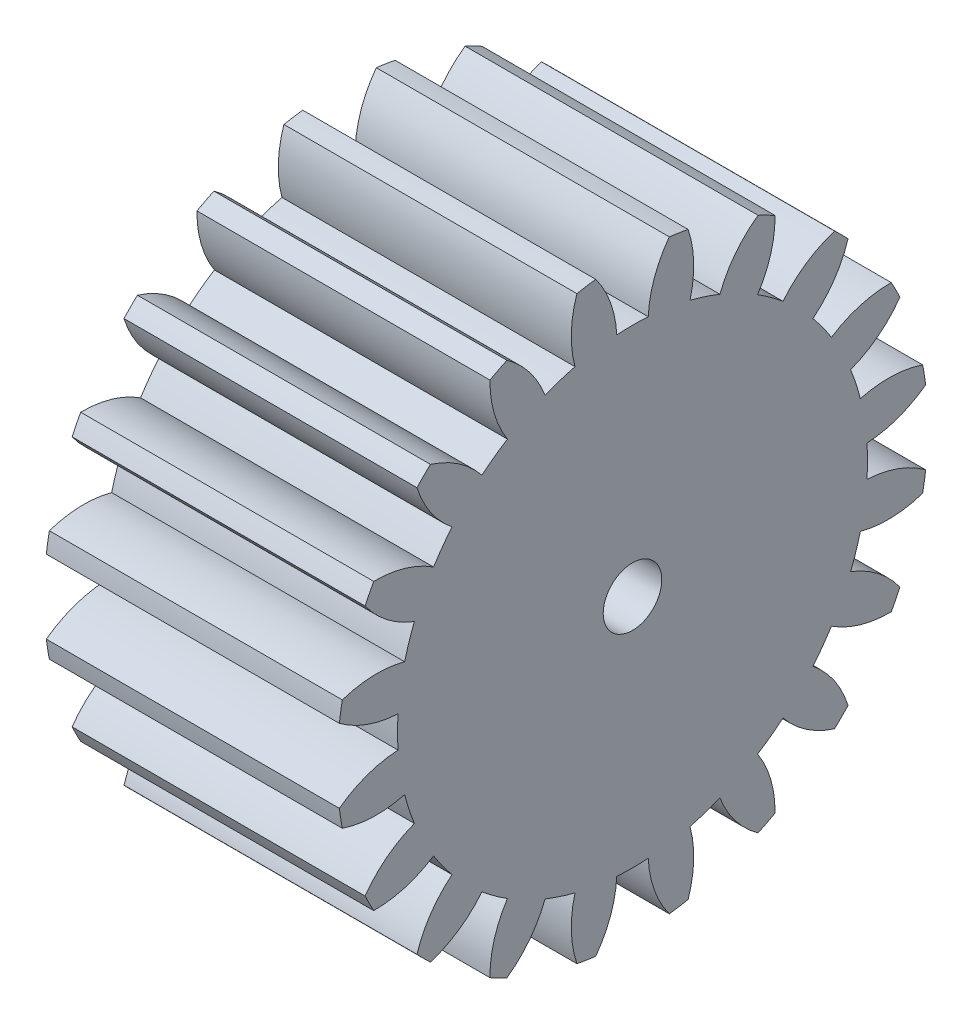
SolidWorks part; units mm, degrees
ref_plane "Plane1" through (0, 0, 0) normal (0, 0, 1) x (1, 0, 0)
ref_plane "Plane2" through (0, 0, 0) normal (0, 1, 0) x (1, 0, 0)
ref_plane "Plane3" through (0, 0, 0) normal (1, 0, 0) x (0, 0, -1)
sketch "HoldingSke" plane through (0, 0, 0) normal (0, 1, 0) x (1, 0, 0)
  line L0 (0, 0) -> (0.6834, -0.2487)
  line L1 (-15, 0) -> (100, 0) construction
  line L2 (0, 0) -> (-2.1039, 2.3779)
  line L3 (0, 0) -> (-11.863, 4.5341)
  line L4 (0, 0) -> (8.1152, 2.9537)
  line L5 (0, 0) -> (-46.8476, -17.4728)
  line L6 (0, 0) -> (-12.4344, -8.3896)
  line L7 (-2.1039, 2.3779) -> (8.6586, 51.2059)
  line L8 (-76.2, 54.61) -> (-75.7, 54.61)
  line L9 (-67.7845, 28.3722) -> (-49.3413, 33.142)
  line L10 (-76.2, 71.12) -> (104.1128, 71.12)
  line L11 (0, 0) -> (-15, 0)
  line L12 (-76.2, 101.6) -> (-76.151, 101.6)
  line L13 (24.9733, 27.94) -> (52.9518, 28.4284)
  line L14 (24.9733, 27.94) -> (24.9743, 27.94)
  line L15 (24.9733, 27.94) -> (100.4006, 29.5858)
  line L16 (-63.627, -1.375) -> (-12.827, -1.375)
  circle A0 centre (0, 0) radius 1.5
  circle A1 centre (0, 0) radius 12.0303
  circle A2 centre (0, 0) radius 37.5
  circle A3 centre (0, 0) radius 1.5
  dimension "MHD" = 24.0605
  dimension "Hub_dia" = 75
  dimension "Bore" = 3
  dimension "MBD" = 3
  dimension "Num_teeth" = 20
  dimension "Pitch" = 0.7273
  dimension "Overall_len" = 50
  dimension "Show_teeth" = 20
  dimension "Thickness" = 15
  dimension "OAL" = 50.0001
  dimension "T_dim" = 0.5
  dimension "Ap" = 14.5
  dimension "H" = 19.05
  dimension "Pitch_radius" = 180.3128
  dimension "Width" = 15
  dimension "Backlash" = 0.049
  dimension "Addendum_fac" = 1
  dimension "Dedendum_fac" = 1.25
  dimension "Clearance_fac" = 0.25
  dimension "Dedendum_add" = 0.001
  dimension "Module" = 1.375
sketch "BasProSke" plane through (0, 0, 0) normal (0, 1, 0) x (1, 0, 0)
  line L0 (-10, 0) -> (60, 0) construction
  line L1 (0, 0) -> (0, 15.125)
  line L2 (0, 0) -> (15, 0)
  line L3 (15, 0) -> (15, 15.125)
  line L4 (15, 15.125) -> (0, 15.125)
  dimension "Thickness" = 15
  dimension "Diameter" = 30.25
revolve "Base-Revolve" add sketch "BasProSke" angle 360 about L0
sketch "TooCutSke" plane through (0, 0, 0) normal (1, 0, 0) x (0, 0, -1)
  line L1 (0, 0) -> (0, 107) construction
  line L2 (0, 0) -> (-1.1645, 13.7006) construction
  line L3 (0, 0) -> (-4.2907, 27.0905) construction
  line L4 (-1.1645, 13.7006) -> (-2.1454, 13.5452) construction
  arc A0 (0.8054, 12.0033) -> (-0.8054, 12.0033) centre (0, 0) ccw
  arc A1 (1.9007, 15.0307) -> (-1.9007, 15.0307) centre (0, 0) ccw
  circle A2 centre (0, 0) radius 13.75 construction
  circle A3 centre (0, 0) radius 13.312 construction
  arc A4 (-0.8054, 12.0033) -> (-1.9007, 15.0307) centre (-6.2985, 11.7277) ccw
  arc A5 (1.9007, 15.0307) -> (0.8054, 12.0033) centre (6.2985, 11.7277) ccw
  dimension "Root_dia" = 24.0605
  dimension "Overcut_dia" = 30.3008
  dimension "Pitch_dia" = 27.5
  dimension "Base_dia" = 26.6241
  dimension "Flank_rad" = 5.5
  dimension "Half_ang" = 9
  dimension "Half_CT" = 0.9931
extrude "ToothCut" cut sketch "TooCutSke" along normal through all
fillet "Breaks" [suppressed] radius 0.0275
fillet "RootFillets" [suppressed] radius 0.3448
pattern_circular "TeethCuts" count 20 over 360 about axis through (0, 0, 0) along (1, 0, 0) of "ToothCut", "RootFillets", "Breaks"
sketch "HubNeaOneSke" plane through (0, 0, 0) normal (-1, 0, 0) x (0, 0, 1)
  circle A0 centre (0, 0) radius 12.0303
  dimension "Diameter" = 24.0605
extrude "HubNearOne" [suppressed] add sketch "HubNeaOneSke" along normal blind 35.0001
sketch "HubNeaBotSke" plane through (0, 0, 0) normal (-1, 0, 0) x (0, 0, 1)
  circle A0 centre (0, 0) radius 12.0303
  dimension "Diameter" = 24.0605
extrude "HubNearBoth" [suppressed] add sketch "HubNeaBotSke" along normal blind 17.5
ref_plane "FarPln" through (15, 0, 0) normal (1, 0, 0) x (0, 0, -1)
sketch "HubFarSke" plane through (15, 0, 0) normal (1, 0, 0) x (0, 0, -1)
  circle A0 centre (0, 0) radius 12.0303
  dimension "Diameter" = 24.0605
extrude "HubFar" [suppressed] add sketch "HubFarSke" along normal blind 17.5
sketch "BorSke" plane through (0, 0, 0) normal (1, 0, 0) x (0, 0, -1)
  circle A0 centre (0, 0) radius 1.5
  dimension "Diameter" = 3
extrude "Bore" cut sketch "BorSke" along normal mid plane 100.0001
sketch "KeySke" plane through (0, 0, 0) normal (1, 0, 0) x (0, 0, -1)
  line L0 (-0.6, 0) -> (-0.6, 2)
  line L1 (-0.6, 2) -> (0.6, 2)
  line L2 (0.6, 2) -> (0.6, 0)
  line L3 (0, 0) -> (0, 34) construction
  line L4 (-0.6, 0) -> (0.6, 0)
  dimension "Offset" = 2
  dimension "Width" = 1.2
extrude "Keyway" [suppressed] cut sketch "KeySke" along normal mid plane 100.0001
pattern_circular "Keyway2" [suppressed] count 2 every 90 about axis through (-10, 0, 0) along (1, 0, 0)
equation "' \"Module@HoldingSke\" = 6.35"
equation "' \"Num_teeth@HoldingSke\" = 12"
equation "' \"Ap@HoldingSke\" =  20"
equation "' \"Ap@HoldingSke\" = 20"
equation "' \"Width@HoldingSke\" = 0.5 * 25.4"
equation "' \"Hub_dia@HoldingSke\"= 1 * 25.4"
equation "' \"Hub_dia@HoldingSke\" = 1 * 25.4"
equation "' \"Overall_len@HoldingSke\" = 1.0 * 25.4"
equation "' \"Bore@HoldingSke\" = 0.75 * 25.4"
equation "' \"T_dim@HoldingSke\" = 0.1 * 25.4"
equation "' \"Width@KeySke\" = 0.25 * 25.4"
equation "' \"Show_teeth@HoldingSke\" = 13"
equation "' \"Backlash@HoldingSke\" = 0.009 * 25.4"
equation "' \"Addendum_fac@HoldingSke\" = 1.0"
equation "' \"Dedendum_fac@HoldingSke\" = 1.25"
equation "' \"Dedendum_add@HoldingSke\" = 0.00005 * 25.4"
equation "' \"Clearance_fac@HoldingSke\" = 0.25"
equation "\"Pitch@HoldingSke\" = 1 / \"Module@HoldingSke\""
equation "\"Overcut_dia@TooCutSke\" = (\"Num_teeth@HoldingSke\" + 2 * \"Addendum_fac@HoldingSke\") / \"Pitch@HoldingSke\" + 0.002 * 25.4"
equation "\"Pitch_dia@TooCutSke\" = \"Num_teeth@HoldingSke\" / \"Pitch@HoldingSke\""
equation "\"Base_dia@TooCutSke\" = \"Num_teeth@HoldingSke\" / \"Pitch@HoldingSke\" * cos((\"Ap@HoldingSke\"  * 3.14159265 / 180))"
equation "\"Root_dia@TooCutSke\" = (\"Num_teeth@HoldingSke\" + 2) / \"Pitch@HoldingSke\" - 2 * (\"Addendum_fac@HoldingSke\" + \"Dedendum_fac@HoldingSke\") / \"Pitch@HoldingSke\" - \"Dedendum_add@HoldingSke\" * 2"
equation "\"Half_ang@TooCutSke\" = 180 / \"Num_teeth@HoldingSke\""
equation "\"Half_CT@TooCutSke\" = \"Num_teeth@HoldingSke\" / \"Pitch@HoldingSke\" * sin((3.14159265 / 2 / \"Num_teeth@HoldingSke\")) / 2 - 7 * \"Backlash@HoldingSke\" / 4"
equation "\"Flank_rad@TooCutSke\" = \"Num_teeth@HoldingSke\" / \"Pitch@HoldingSke\" / 5"
equation "\"Radius@RootFillets\" = \"Clearance_fac@HoldingSke\" / \"Pitch@HoldingSke\" + \"Dedendum_add@HoldingSke\""
equation "\"Break_rad@Breaks\" = 0.02 / \"Pitch@HoldingSke\""
equation "\"Thickness@HoldingSke\" = \"Width@HoldingSke\""
equation "\"OAL@HoldingSke\" = \"Thickness@HoldingSke\""
equation "\"MHD@HoldingSke\" = (\"Num_teeth@HoldingSke\" + 2) / \"Pitch@HoldingSke\" - 2 * (\"Addendum_fac@HoldingSke\" + \"Dedendum_fac@HoldingSke\")  / \"Pitch@HoldingSke\" - \"Dedendum_add@HoldingSke\" * 2"
equation "\"MBD@HoldingSke\" = (\"Num_teeth@HoldingSke\" + 2) / \"Pitch@HoldingSke\" - 2 * (\"Addendum_fac@HoldingSke\" + \"Dedendum_fac@HoldingSke\")  / \"Pitch@HoldingSke\" - \"Dedendum_add@HoldingSke\" * 2 - 0.002 * 25.4"
equation "\"MHD@HoldingSke\" = ((sgn( \"MHD@HoldingSke\" - \"Hub_dia@HoldingSke\" )-1)*( \"MHD@HoldingSke\" - \"Hub_dia@HoldingSke\" ))/-2+ \"Hub_dia@HoldingSke\""
equation "\"MBD@HoldingSke\" = ((sgn( \"MBD@HoldingSke\" - \"Bore@HoldingSke\" )-1)*( \"MBD@HoldingSke\" - \"Bore@HoldingSke\" ))/-2+ \"Bore@HoldingSke\""
equation "\"OAL@HoldingSke\" = ((sgn( \"OAL@HoldingSke\" - \"Overall_len@HoldingSke\" )+1)*( \"OAL@HoldingSke\" - \"Overall_len@HoldingSke\" ))/2 + \"Overall_len@HoldingSke\" + 0.000002 * 25.4"
equation "\"Num_teeth@TeethCuts\" = int( \"Show_teeth@HoldingSke\" ) + 1"
equation "\"Num_teeth@TeethCuts\" = ((sgn( \"Num_teeth@TeethCuts\" - \"Num_teeth@HoldingSke\" )-1)*( \"Num_teeth@TeethCuts\" - \"Num_teeth@HoldingSke\" ))/-2+ \"Num_teeth@HoldingSke\""
equation "\"Num_teeth@TeethCuts\" = ((sgn( \"Num_teeth@TeethCuts\" - 2.0)+1)*( \"Num_teeth@TeethCuts\" - 2.0))/2 +2.0"
equation "\"Angle@TeethCuts\" = 360.0 / \"Num_teeth@HoldingSke\""
equation "\"Diameter@BasProSke\" = (\"Num_teeth@HoldingSke\" + 2 * \"Addendum_fac@HoldingSke\") / \"Pitch@HoldingSke\""
equation "\"Thickness@BasProSke\"  = \"Thickness@HoldingSke\""
equation "' \"Fillet_rad@BasProSke\" =  \"Thickness@HoldingSke\" * 0.05"
equation "' \"Fillet_rad@BasProSke\" = \"Thickness@HoldingSke\" * 0.05"
equation "\"MHD@HoldingSke\" = ((sgn( \"MHD@HoldingSke\" - \"Root_dia@TooCutSke\" )-1)*( \"MHD@HoldingSke\" - \"Root_dia@TooCutSke\" ))/-2+ \"Root_dia@TooCutSke\""
equation "\"Diameter@HubNeaOneSke\" = \"MHD@HoldingSke\""
equation "\"Length@HubNearOne\" = \"OAL@HoldingSke\" - \"Thickness@BasProSke\""
equation "\"Diameter@HubNeaBotSke\" = \"MHD@HoldingSke\""
equation "\"Length@HubNearBoth\" = ( \"OAL@HoldingSke\" - \"Thickness@BasProSke\" ) / 2.0"
equation "\"Thickness@FarPln\" = \"Thickness@BasProSke\""
equation "\"Diameter@HubFarSke\" = \"MHD@HoldingSke\""
equation "\"Length@HubFar\" = ( \"OAL@HoldingSke\" - \"Thickness@BasProSke\" ) / 2.0"
equation "\"Diameter@BorSke\" = \"MBD@HoldingSke\""
equation "\"D1@Bore\" = \"OAL@HoldingSke\" * 2.0"
equation "\"D1@Keyway\" = \"OAL@HoldingSke\" * 2.0"
equation "\"Offset@KeySke\" = \"T_dim@HoldingSke\" + \"MBD@HoldingSke\" / 2.0"
